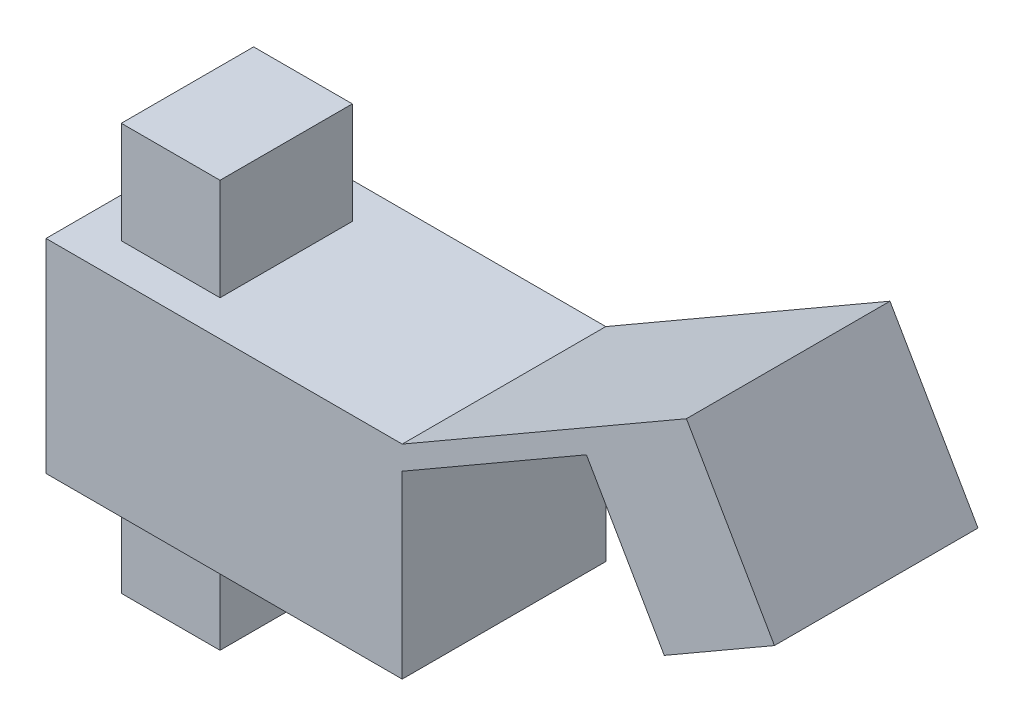
SolidWorks part; units mm, degrees
ref_plane "Alzado" through (0, 0, 0) normal (0, 0, 1) x (1, 0, 0)
ref_plane "Planta" through (0, 0, 0) normal (0, 1, 0) x (1, 0, 0)
ref_plane "Vista lateral" through (0, 0, 0) normal (1, 0, 0) x (0, 0, -1)
sketch "Croquis1" plane through (0, 0, 0) normal (0, 0, 1) x (1, 0, 0)
  line L0 (0, 75.7222) -> (0, -75.7222) construction
  line L1 (-103.9404, 0) -> (103.9404, 0) construction
  line L2 (72.1845, 62.3029) -> (93.8351, 74.8029) construction
  line L3 (73.9881, 84.179) -> (92.0316, 52.9268) construction
  line L5 (65.4243, 73.9883) -> (80.7217, 47.4924)
  line L6 (85.0749, 89.9524) -> (102.3724, 59.9924)
  line L8 (80.7217, 47.4924) -> (102.3724, 59.9924)
  line L9 (29.2269, 57.7086) -> (-40.7731, 57.7086)
  line L10 (-40.7731, 57.7086) -> (-40.7731, 17.7086)
  line L11 (-40.7731, 17.7086) -> (29.2269, 17.7086)
  line L18 (29.2269, 53.0898) -> (65.4243, 73.9883)
  line L19 (29.2269, 57.7086) -> (85.0749, 89.9524)
  line L21 (29.2269, 17.7086) -> (29.2269, 53.0898)
  point P5 (0, 0)
  point P6 (0, 0)
  point P9 (0, 0)
  point P11 (83.0098, 68.5529)
  point P12 (83.0098, 68.5529)
  dimension "D1" = 120
  dimension "D2" = 52.0024
  dimension "D3" = 25
  dimension "D4" = 17.5
  dimension "D5" = 70
  dimension "D6" = 40
  dimension "D7" = 12.5
extrude "Saliente-Extruir1" add sketch "Croquis1" along normal mid plane 40
sketch "Croquis2" plane through (0, 57.7086, 0) normal (0, 1, 0) x (1, 0, 0)
  line L0 (-40.7731, 0) -> (29.2269, 0) construction
  line L1 (-40.7731, -20) -> (-40.7731, 20) construction
  line L2 (29.2269, -20) -> (29.2269, 20) construction
  line L3 (-5.7731, 20) -> (-5.7731, -20) construction
  line L4 (29.2269, 20) -> (-40.7731, 20) construction
  line L5 (29.2269, -20) -> (-40.7731, -20) construction
  line L6 (-23.2731, 20) -> (-23.2731, -20) construction
  line L7 (-32.9714, -13) -> (-13.5749, -13)
  line L8 (-32.9714, 13) -> (-13.5749, 13)
  line L9 (-32.9714, -13) -> (-32.9714, 13)
  line L10 (-13.5749, -13) -> (-13.5749, 13)
  point P16 (-23.2731, -13)
  dimension "D1" = 17.5
  dimension "D2" = 7
  dimension "D3" = 26
extrude "Saliente-Extruir2" add sketch "Croquis2" along normal blind 20 and the other way blind 60 from surface at 0 starting at face at (-5.7731, 57.7086, 0)
sketch "Croquis4" plane through (0, 0, 20) normal (0, 0, 1) x (1, 0, 0)
  line L19 (-38.7731, 55.7086) -> (27.2269, 55.7086)
  line L22 (27.2269, 55.7086) -> (27.2269, 19.7086)
  line L35 (27.2269, 19.7086) -> (27.2269, 53.0898)
  line L36 (-38.7731, 19.7086) -> (27.2269, 19.7086)
  line L37 (-38.7731, 55.7086) -> (-38.7731, 19.7086)
  line L38 (29.2269, 55.7086) -> (-38.7731, 55.7086)
  line L40 (-38.7731, 19.7086) -> (27.2269, 19.7086)
  line L41 (-38.7731, 55.7086) -> (-38.7731, 19.7086)
  dimension "D2" = 2
extrude "Cortar-Extruir1" cut sketch "Croquis4" against normal blind 18 and the other way blind 18 from offset 20 offset against normal yes
sketch "Croquis6" plane through (0, 0, 13) normal (0, 0, 1) x (1, 0, 0)
  line L4 (-28.9714, 73.7086) -> (-28.9714, 1.7086)
  line L5 (-17.5749, 73.7086) -> (-17.5749, 1.7086)
  line L6 (-28.9714, 1.7086) -> (-17.5749, 1.7086)
  line L7 (-32.9714, -2.2914) -> (-13.5749, -2.2914) construction
  line L8 (-28.9714, 61.7086) -> (-17.5749, 61.7086)
  line L9 (-17.5749, 61.7086) -> (-17.5749, 73.7086)
  line L10 (-17.5749, 73.7086) -> (-28.9714, 73.7086)
  line L11 (-28.9714, 73.7086) -> (-28.9714, 61.7086)
  line L14 (-17.5749, 73.7086) -> (-28.9714, 73.7086)
  dimension "D2" = 4
  dimension "D1" = 4
extrude "Cortar-Extruir2" cut sketch "Croquis6" against normal blind 9 and the other way blind 9 from offset 13
